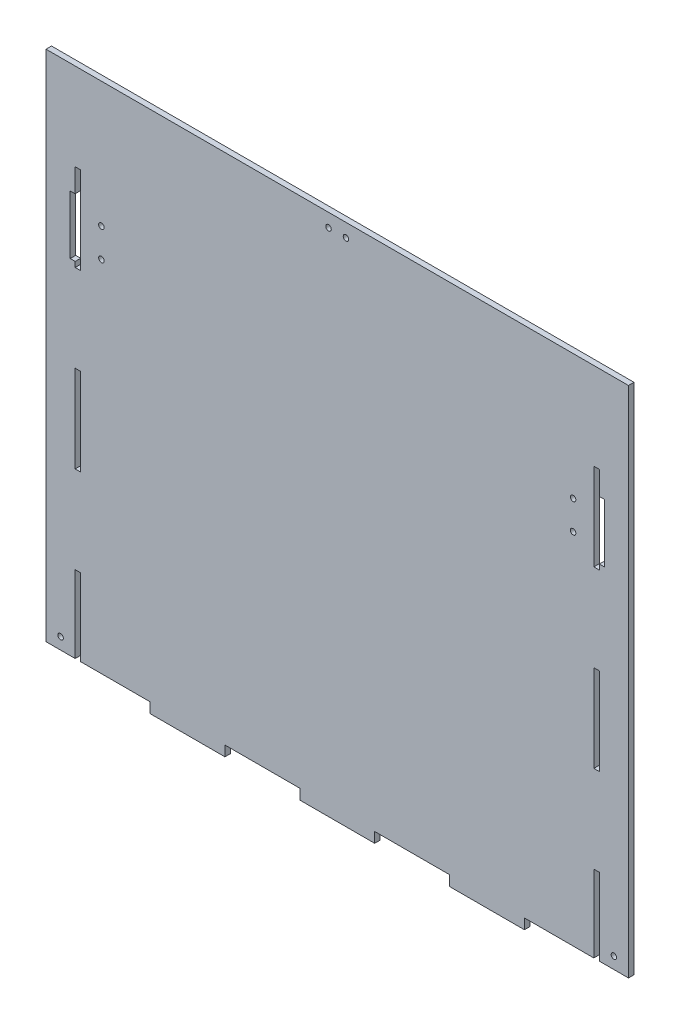
SolidWorks part; units mm, degrees
ref_plane "Front Plane" through (0, 0, 0) normal (0, 0, 1) x (1, 0, 0)
ref_plane "Top Plane" through (0, 0, 0) normal (0, 1, 0) x (1, 0, 0)
ref_plane "Right Plane" through (0, 0, 0) normal (1, 0, 0) x (0, 0, -1)
sketch "Sketch1" plane through (0, 0, 0) normal (0, 0, 1) x (1, 0, 0)
  line L1 (0, 139.7) -> (0, -139.7) construction
  line L2 (-139.7, 139.7) -> (139.7, 139.7)
  line L3 (-139.7, 139.7) -> (-139.7, -139.7)
  line L4 (-139.7, -139.7) -> (139.7, -139.7)
  line L5 (139.7, 139.7) -> (139.7, -139.7)
  line L6 (-139.7, 0) -> (139.7, 0) construction
  line L7 (-139.7, 92.202) -> (-139.7, 44.704)
  line L8 (-139.7, 139.7) -> (-142.6972, 139.7)
  line L96 (-139.7, 139.7) -> (-139.7, 92.202)
  line L97 (-139.7, 92.202) -> (-142.6972, 92.202)
  line L98 (-142.6972, 139.7) -> (-142.6972, 92.202)
  line L99 (139.7, 139.7) -> (142.6972, 139.7)
  line L100 (139.7, 139.7) -> (139.7, 92.202)
  line L101 (139.7, 92.202) -> (142.6972, 92.202)
  line L102 (142.6972, 139.7) -> (142.6972, 92.202)
  line L103 (-101.9266, -139.7) -> (-142.6972, -139.7)
  line L104 (-101.9266, -139.7) -> (-101.9266, -145.288)
  line L105 (-101.9266, -145.288) -> (-142.6972, -145.288)
  line L106 (-142.6972, -139.7) -> (-142.6972, -145.288)
  line L107 (-139.7, 92.202) -> (-142.6972, 92.202)
  line L108 (-142.6972, 92.202) -> (-142.6972, 44.704)
  line L109 (-139.7, 44.704) -> (-142.6972, 44.704)
  line L110 (139.7, 92.202) -> (139.7, 44.704)
  line L111 (139.7, 92.202) -> (142.6972, 92.202)
  line L112 (142.6972, 92.202) -> (142.6972, 44.704)
  line L113 (139.7, 44.704) -> (142.6972, 44.704)
  line L114 (-139.7, 44.704) -> (-139.7, -2.794)
  line L115 (-139.7, 44.704) -> (-142.6972, 44.704)
  line L116 (-142.6972, 44.704) -> (-142.6972, -2.794)
  line L117 (-139.7, -2.794) -> (-142.6972, -2.794)
  line L118 (139.7, 44.704) -> (139.7, -2.794)
  line L119 (139.7, 44.704) -> (142.6972, 44.704)
  line L120 (142.6972, 44.704) -> (142.6972, -2.794)
  line L121 (139.7, -2.794) -> (142.6972, -2.794)
  line L122 (-139.7, -2.794) -> (-139.7, -50.292)
  line L123 (-139.7, -2.794) -> (-142.6972, -2.794)
  line L124 (-142.6972, -2.794) -> (-142.6972, -50.292)
  line L125 (-139.7, -50.292) -> (-142.6972, -50.292)
  line L126 (139.7, -2.794) -> (139.7, -50.292)
  line L127 (139.7, -2.794) -> (142.6972, -2.794)
  line L128 (142.6972, -2.794) -> (142.6972, -50.292)
  line L129 (139.7, -50.292) -> (142.6972, -50.292)
  line L130 (-139.7, -50.292) -> (-139.7, -97.79)
  line L131 (-139.7, -50.292) -> (-142.6972, -50.292)
  line L132 (-142.6972, -50.292) -> (-142.6972, -97.79)
  line L133 (-139.7, -97.79) -> (-142.6972, -97.79)
  line L134 (139.7, -50.292) -> (139.7, -97.79)
  line L135 (139.7, -50.292) -> (142.6972, -50.292)
  line L136 (142.6972, -50.292) -> (142.6972, -97.79)
  line L137 (139.7, -97.79) -> (142.6972, -97.79)
  line L138 (-139.7, -97.79) -> (-139.7, -145.288)
  line L139 (-139.7, -97.79) -> (-142.6972, -97.79)
  line L140 (-142.6972, -97.79) -> (-142.6972, -145.288)
  line L141 (-139.7, -145.288) -> (-142.6972, -145.288)
  line L142 (139.7, -97.79) -> (139.7, -145.288)
  line L143 (139.7, -97.79) -> (142.6972, -97.79)
  line L144 (142.6972, -97.79) -> (142.6972, -145.288)
  line L145 (139.7, -145.288) -> (142.6972, -145.288)
  line L146 (-61.1559, -139.7) -> (-61.1559, -145.288)
  line L147 (-61.1559, -139.7) -> (-101.9266, -139.7)
  line L148 (-101.9266, -139.7) -> (-101.9266, -145.288)
  line L149 (-61.1559, -145.288) -> (-101.9266, -145.288)
  line L150 (-20.3853, -139.7) -> (-20.3853, -145.288)
  line L151 (-20.3853, -139.7) -> (-61.1559, -139.7)
  line L152 (-61.1559, -139.7) -> (-61.1559, -145.288)
  line L153 (-20.3853, -145.288) -> (-61.1559, -145.288)
  line L154 (20.3853, -139.7) -> (20.3853, -145.288)
  line L155 (20.3853, -139.7) -> (-20.3853, -139.7)
  line L156 (-20.3853, -139.7) -> (-20.3853, -145.288)
  line L157 (20.3853, -145.288) -> (-20.3853, -145.288)
  line L158 (61.1559, -139.7) -> (61.1559, -145.288)
  line L159 (61.1559, -139.7) -> (20.3853, -139.7)
  line L160 (20.3853, -139.7) -> (20.3853, -145.288)
  line L161 (61.1559, -145.288) -> (20.3853, -145.288)
  line L162 (101.9266, -139.7) -> (101.9266, -145.288)
  line L163 (101.9266, -139.7) -> (61.1559, -139.7)
  line L164 (61.1559, -139.7) -> (61.1559, -145.288)
  line L165 (101.9266, -145.288) -> (61.1559, -145.288)
  line L166 (142.6972, -139.7) -> (142.6972, -145.288)
  line L167 (142.6972, -139.7) -> (101.9266, -139.7)
  line L168 (101.9266, -139.7) -> (101.9266, -145.288)
  line L169 (142.6972, -145.288) -> (101.9266, -145.288)
  point P8 (0, 0)
  dimension "D1" = 279.4
  dimension "D2" = 279.4
  dimension "D3" = 285.3944
  dimension "D4" = 284.988
  dimension "D6" = 47.498
  dimension "D8" = 40.7706
  dimension "D5" = 6
  dimension "D7" = 7
extrude "Boss-Extrude1" add sketch "Sketch1" along normal mid plane 2.9972 contours L5 L2 L3 L4 | L133 L3 L125 L132 | L149 L146 L4 L104 | L157 L154 L4 L150 | L165 L162 L4 L158 | L5 L137 L136 L129 | L5 L121 L120 L113 | L102 L99 L5 L101 | L117 L3 L109 L116 | L8 L98 L97 L3
sketch "Sketch2" plane through (0, 0, 1.4986) normal (0, 0, 1) x (1, 0, 0)
  line L0 (38.1, 114.3) -> (-38.1, 114.3) construction
  line L1 (38.1, 101.6) -> (-38.1, 101.6)
  line L2 (38.1, 127) -> (-38.1, 127)
  line L3 (-142.6972, 139.7) -> (142.6972, 139.7) construction
  arc A0 (38.1, 101.6) -> (38.1, 127) centre (38.1, 114.3) ccw
  arc A1 (-38.1, 127) -> (-38.1, 101.6) centre (-38.1, 114.3) ccw
  point P2 (0, 114.3)
  dimension "D1" = 25.4
  dimension "D2" = 76.2
  dimension "D3" = 12.7
extrude "Cut-Extrude1" [suppressed] cut sketch "Sketch2" against normal through all
sketch "Sketch3" plane through (0, 0, 1.4986) normal (0, 0, 1) x (1, 0, 0)
  line L0 (-128.4097, 71.374) -> (-128.4097, 55.626) construction
  line L1 (128.4097, 71.374) -> (128.4097, 55.626) construction
  line L2 (-128.4097, 63.5) -> (128.4097, 63.5) construction
  line L3 (0, 0) -> (0, 63.5) construction
  line L4 (-142.6972, 139.7) -> (-142.6972, 92.202) construction
  line L5 (-142.6972, 139.7) -> (142.6972, 139.7) construction
  circle A0 centre (-128.4097, 71.374) radius 1.5
  circle A1 centre (-128.4097, 55.626) radius 1.5
  circle A2 centre (128.4097, 71.374) radius 1.5
  circle A3 centre (128.4097, 55.626) radius 1.5
  dimension "D1" = 3
  dimension "D2" = 15.748
  dimension "D3" = 14.2875
  dimension "D4" = 76.2
extrude "Cut-Extrude2" cut sketch "Sketch3" against normal through all
sketch "Sketch4" plane through (0, 0, 1.4986) normal (0, 0, 1) x (1, 0, 0)
  line L0 (101.9266, -139.7) -> (139.7, -139.7) construction
  line L1 (-142.6972, 139.7) -> (-158.5722, 139.7)
  line L2 (-142.6972, 139.7) -> (-142.6972, -139.7)
  line L3 (-142.6972, -139.7) -> (-158.5722, -139.7)
  line L4 (-158.5722, 139.7) -> (-158.5722, -139.7)
  line L5 (142.6972, 139.7) -> (158.5722, 139.7)
  line L6 (142.6972, 139.7) -> (142.6972, -139.7)
  line L7 (142.6972, -139.7) -> (158.5722, -139.7)
  line L8 (158.5722, 139.7) -> (158.5722, -139.7)
  line L9 (145.3972, 63.5) -> (128.4097, 63.5) construction
  line L10 (-142.6972, 79.4385) -> (-145.3972, 79.4385)
  line L11 (-142.6972, 79.4385) -> (-142.6972, 47.5615)
  line L12 (-142.6972, 47.5615) -> (-145.3972, 47.5615)
  line L13 (-145.3972, 79.4385) -> (-145.3972, 47.5615)
  line L14 (142.6972, 79.4385) -> (145.3972, 79.4385)
  line L15 (142.6972, 79.4385) -> (142.6972, 47.5615)
  line L16 (142.6972, 47.5615) -> (145.3972, 47.5615)
  line L17 (145.3972, 79.4385) -> (145.3972, 47.5615)
  line L18 (128.4097, 55.626) -> (128.4097, 71.374) construction
  line L19 (-150.6347, -133.35) -> (-150.6347, -139.7) construction
  line L20 (-139.7, -139.7) -> (-101.9266, -139.7) construction
  line L21 (150.6347, -133.35) -> (-150.6347, -133.35) construction
  line L22 (0, -133.35) -> (0, 0) construction
  circle A0 centre (-150.6347, -133.35) radius 1.5
  circle A1 centre (150.6347, -133.35) radius 1.5
  point P27 (128.4097, 63.5)
  line M15 (142.6972, 92.202) -> (142.6972, 139.7)
  line M17 (-142.6972, 139.7) -> (-142.6972, 92.202)
  line M21 (-142.6972, 44.704) -> (-142.6972, -2.794)
  line M25 (-142.6972, -50.292) -> (-142.6972, -97.79)
  line M43 (142.6972, -97.79) -> (142.6972, -50.292)
  line M47 (142.6972, -2.794) -> (142.6972, 44.704)
  dimension "D6" = 3
  dimension "D1" = 15.875
  dimension "D2" = 31.877
  dimension "D3" = 2.7
  dimension "D5" = 6.35
extrude "Boss-Extrude2" add sketch "Sketch4" against normal up to surface (2.9972 mm away) contours L13 L10 L2 L1 L4 L3 L12 M17 M25 M21 | L14 L17 L16 L6 L7 L8 L5 M47 M43 M15
sketch "Sketch5" plane through (0, 0, 1.4986) normal (0, 0, 1) x (1, 0, 0)
  line L0 (-4.7625, 132.3975) -> (4.7625, 132.3975) construction
  line L1 (0, 132.3975) -> (0, 139.7) construction
  line L2 (-158.5722, 139.7) -> (158.5722, 139.7) construction
  circle A0 centre (-4.7625, 132.3975) radius 1.5
  circle A1 centre (4.7625, 132.3975) radius 1.5
  dimension "D1" = 3
  dimension "D2" = 9.525
  dimension "D3" = 7.3025
extrude "Cut-Extrude3" cut sketch "Sketch5" against normal through all
equation "\"wallthickness\"= .118in"
equation "\"floorThickness\"= .220in"
equation "\"D3@Sketch1\"=\"wallthickness\"*2+\"D1@Sketch1\""
equation "\"D4@Sketch1\"=\"floorThickness\"+\"D2@Sketch1\""
equation "\"D6@Sketch1\"=\"D4@Sketch1\"/\"D5@Sketch1\""
equation "\"D8@Sketch1\"=\"D3@Sketch1\"/\"D7@Sketch1\""
equation "\"D1@Boss-Extrude1\"=\"wallthickness\""
